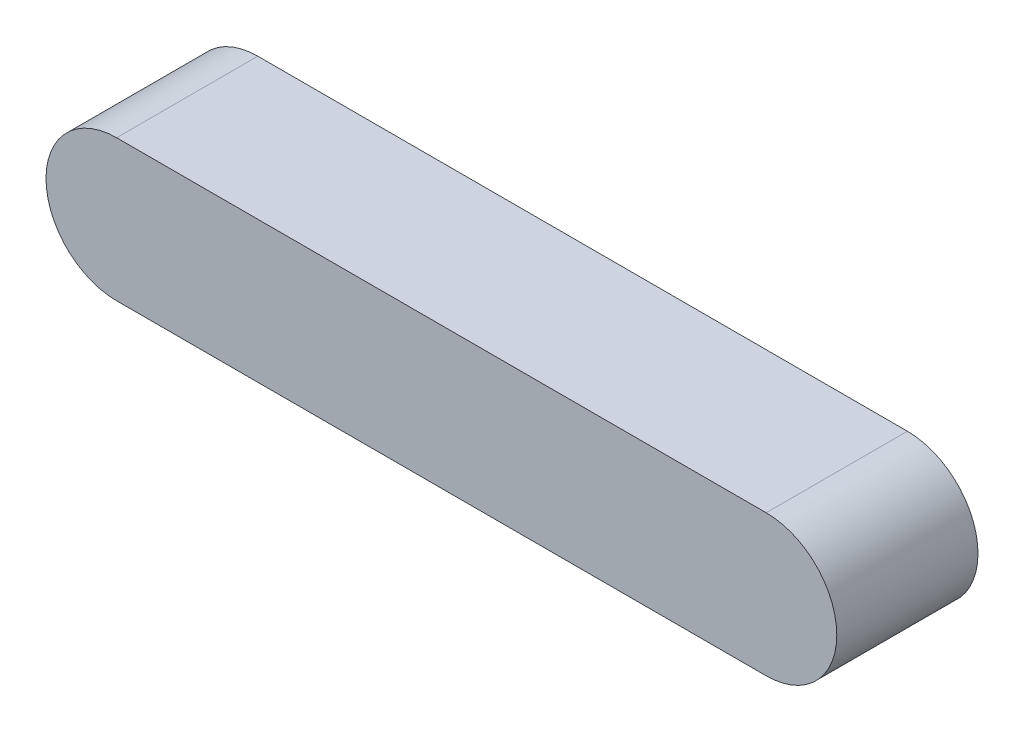
SolidWorks part; units mm, degrees
ref_plane "Front Plane" through (0, 0, 0) normal (0, 0, 1) x (1, 0, 0)
ref_plane "Top Plane" through (0, 0, 0) normal (0, 1, 0) x (1, 0, 0)
ref_plane "Right Plane" through (0, 0, 0) normal (1, 0, 0) x (0, 0, -1)
sketch "Sketch2" plane through (0, 0, 0) normal (0, 0, 1) x (1, 0, 0)
  line L0 (0, 0) -> (53.535, 0) construction
  line L1 (26.7675, 0) -> (49.7675, 0) construction
  line L2 (26.7675, 2.5) -> (49.7675, 2.5)
  line L3 (26.7675, -2.5) -> (49.7675, -2.5)
  arc A0 (26.7675, 2.5) -> (26.7675, -2.5) centre (26.7675, 0) ccw
  arc A1 (49.7675, -2.5) -> (49.7675, 2.5) centre (49.7675, 0) ccw
  point P5 (38.2675, 0)
  point P10 (24.2675, 0)
  point P11 (52.2675, 0)
  dimension "D4" = 2.5
  dimension "D5" = 2.5
  dimension "D1" = 5
  dimension "D2" = 23
  dimension "D3" = 28
extrude "Boss-Extrude2" add sketch "Sketch2" along normal blind 5
